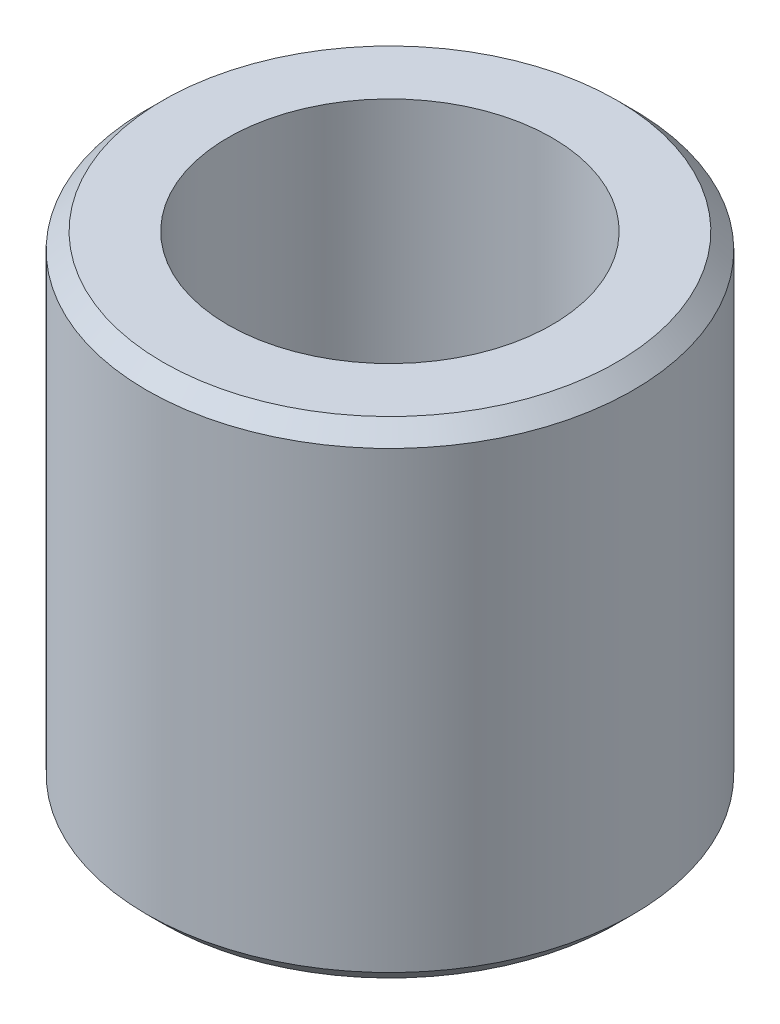
SolidWorks part; units mm, degrees
ref_plane "Front Plane" through (0, 0, 0) normal (0, 0, 1) x (1, 0, 0)
ref_plane "Top Plane" through (0, 0, 0) normal (0, 1, 0) x (1, 0, 0)
ref_plane "Right Plane" through (0, 0, 0) normal (1, 0, 0) x (0, 0, -1)
sketch "Sketch1" plane through (0, 0, 0) normal (0, 1, 0) x (1, 0, 0)
  circle A0 centre (0, 0) radius 15
  dimension "D1" = 30
extrude "Boss-Extrude2" add sketch "Sketch1" along normal mid plane 30
sketch "Sketch2" plane through (0, -15, 0) normal (0, -1, 0) x (1, 0, 0)
  circle A0 centre (0, 0) radius 10
  dimension "D1" = 20
extrude "Cut-Extrude1" cut sketch "Sketch2" against normal blind 36
chamfer "Chamfer2" distance 1 angle 45 2 edges at (0, -15, 15) (0, 15, 15)
